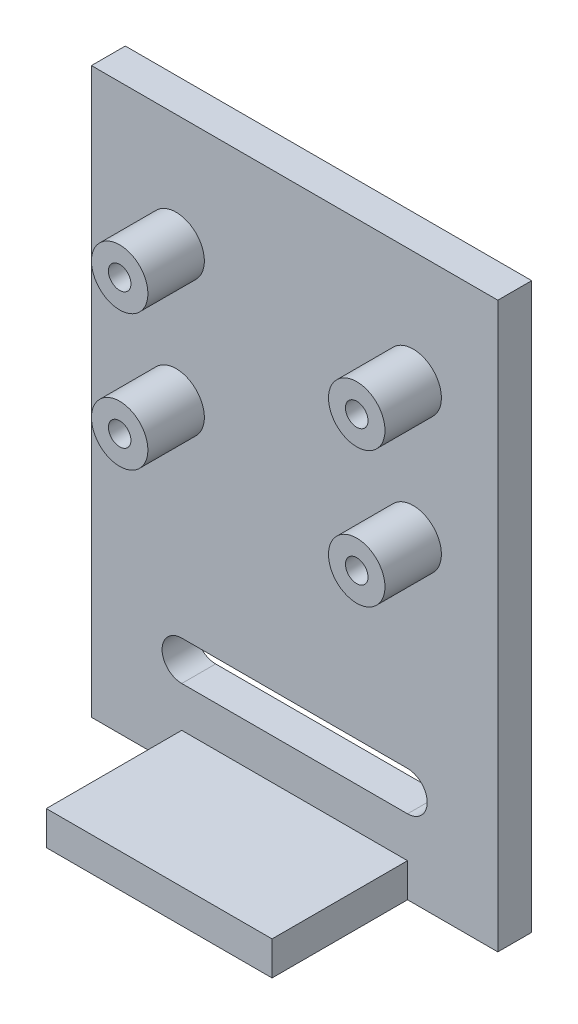
SolidWorks part; units mm, degrees
ref_plane "Front Plane" through (0, 0, 0) normal (0, 0, 1) x (1, 0, 0)
ref_plane "Top Plane" through (0, 0, 0) normal (0, 1, 0) x (1, 0, 0)
ref_plane "Right Plane" through (0, 0, 0) normal (1, 0, 0) x (0, 0, -1)
sketch "Sketch1" plane through (0, 0, 0) normal (0, 0, 1) x (1, 0, 0)
  line L1 (11.6329, 19.9422) -> (-24.3671, 19.9422)
  line L2 (11.6329, 19.9422) -> (11.6329, -30.0578)
  line L3 (11.6329, -30.0578) -> (-24.3671, -30.0578)
  line L4 (-24.3671, 19.9422) -> (-24.3671, -30.0578)
  dimension "D1" = 50
  dimension "D2" = 36
  dimension "D3" = 36
  dimension "D4" = 50
extrude "Boss-Extrude1" add sketch "Sketch1" along normal blind 3
sketch "Sketch2" plane through (0, 0, 3) normal (0, 0, 1) x (1, 0, 0)
  line L0 (3.6329, -30.0578) -> (3.6329, -27.0578)
  line L1 (-24.3671, -30.0578) -> (11.6329, -30.0578) construction
  line L2 (3.6329, -27.0578) -> (-16.3671, -27.0578)
  line L3 (-16.3671, -27.0578) -> (-16.3671, -30.0578)
  line L4 (11.6329, -30.0578) -> (11.6329, 19.9422) construction
  line L5 (-24.3671, 19.9422) -> (-24.3671, -30.0578) construction
  line L10 (11.6329, -30.0578) -> (11.6329, 19.9422)
  line L11 (11.6329, 19.9422) -> (-24.3671, 19.9422)
  line L12 (-24.3671, 19.9422) -> (-24.3671, -30.0578)
  line L13 (-24.3671, -30.0578) -> (11.6329, -30.0578)
  line L17 (-16.3671, -30.0578) -> (3.6329, -30.0578)
  dimension "D1" = 20
  dimension "D2" = 3
  dimension "D3" = 8
  dimension "D4" = 8
  dimension "D5" = 0
extrude "Boss-Extrude2" add sketch "Sketch2" along normal blind 12
sketch "Sketch4" plane through (0, 0, 3) normal (0, 0, 1) x (1, 0, 0)
  line L0 (-16.3671, -21.7213) -> (3.6329, -21.7213) construction
  line L1 (-16.3671, -19.9804) -> (3.6329, -19.9804)
  line L2 (-16.3671, -23.4623) -> (3.6329, -23.4623)
  line L3 (-24.3671, 19.9422) -> (-24.3671, -30.0578) construction
  line L4 (11.6329, -30.0578) -> (11.6329, 19.9422) construction
  arc A0 (-16.3671, -19.9804) -> (-16.3671, -23.4623) centre (-16.3671, -21.7213) ccw
  arc A1 (3.6329, -23.4623) -> (3.6329, -19.9804) centre (3.6329, -21.7213) ccw
  point P2 (-6.3671, -21.7213)
  dimension "D1" = 20
  dimension "D2" = 8
  dimension "D3" = 8
extrude "Cut-Extrude1" cut sketch "Sketch4" against normal blind 5
sketch "Sketch5" plane through (0, 0, 3) normal (0, 0, 1) x (1, 0, 0)
  line L0 (-24.3671, 19.9422) -> (-24.3671, -30.0578) construction
  line L1 (11.6329, -30.0578) -> (11.6329, 19.9422) construction
  line L2 (11.6329, 19.9422) -> (-24.3671, 19.9422) construction
  circle A0 centre (4.1329, 9.9422) radius 1
  circle A1 centre (-16.8671, 9.9422) radius 1
  circle A2 centre (4.1329, -2.0578) radius 1
  circle A3 centre (-16.8671, -2.0578) radius 1
  circle A4 centre (4.1329, 9.9422) radius 2.5
  circle A5 centre (-16.8671, 9.9422) radius 2.5
  circle A6 centre (-16.8671, -2.0578) radius 2.5
  circle A7 centre (4.1329, -2.0578) radius 2.5
  dimension "D1" = 2
  dimension "D2" = 2
  dimension "D3" = 2
  dimension "D4" = 2
  dimension "D15" = 5
  dimension "D16" = 5
  dimension "D17" = 5
  dimension "D18" = 5
  dimension "D5" = 21
  dimension "D6" = 21
  dimension "D7" = 12
  dimension "D8" = 12
  dimension "D9" = 7.5
  dimension "D10" = 7.5
  dimension "D11" = 7.5
  dimension "D12" = 7.5
  dimension "D13" = 10
  dimension "D14" = 10
extrude "Boss-Extrude4" add sketch "Sketch5" along normal blind 5
